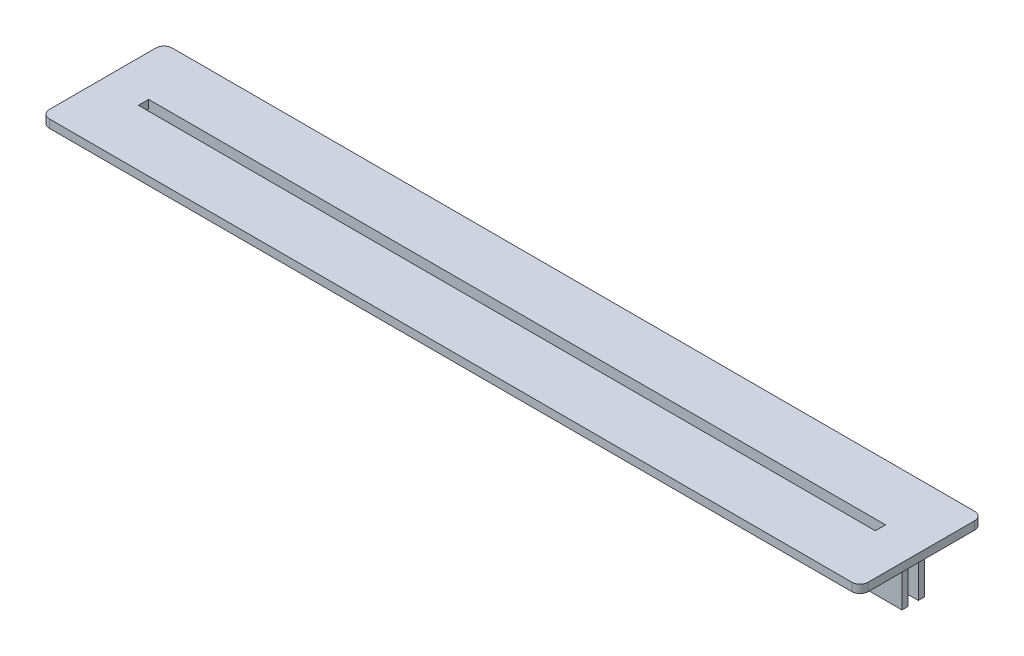
SolidWorks part; units mm, degrees
ref_plane "Front Plane" through (0, 0, 0) normal (0, 0, 1) x (1, 0, 0)
ref_plane "Top Plane" through (0, 0, 0) normal (0, 1, 0) x (1, 0, 0)
ref_plane "Right Plane" through (0, 0, 0) normal (1, 0, 0) x (0, 0, -1)
sketch "Sketch3" plane through (0, 0, 0) normal (0, 1, 0) x (1, 0, 0)
  line L1 (-124.46, 19.05) -> (124.46, 19.05)
  line L2 (-127, 16.51) -> (-127, -16.51)
  line L3 (-124.46, -19.05) -> (124.46, -19.05)
  line L4 (127, 16.51) -> (127, -16.51)
  line L5 (-127, 19.05) -> (127, -19.05) construction
  line L6 (-127, -19.05) -> (127, 19.05) construction
  arc A0 (124.46, -19.05) -> (127, -16.51) centre (124.46, -16.51) ccw
  arc A1 (124.46, 19.05) -> (127, 16.51) centre (124.46, 16.51) cw
  arc A2 (-127, -16.51) -> (-124.46, -19.05) centre (-124.46, -16.51) ccw
  arc A3 (-124.46, 19.05) -> (-127, 16.51) centre (-124.46, 16.51) ccw
  point P0 (0, 0)
  dimension "D3" = 2.54
  dimension "D1" = 254
  dimension "D2" = 38.1
extrude "Boss-Extrude1" add sketch "Sketch3" along normal blind 2.54
sketch "Sketch4" plane through (0, 0, 0) normal (1, 0, 0) x (0, 0, -1)
  line L0 (-16.51, 0) -> (-16.51, -12.7)
  line L1 (-16.51, -12.7) -> (-14.5796, -12.7)
  line L2 (-14.5796, -12.7) -> (-14.5796, 0)
  line L3 (-16.51, 0) -> (16.51, 0) construction
  line L4 (-14.5796, 0) -> (-16.51, 0)
  line L5 (0, 10.2591) -> (0, -16.4007) construction
  line L6 (14.5796, 0) -> (16.51, 0)
  line L7 (14.5796, -12.7) -> (14.5796, 0)
  line L8 (16.51, -12.7) -> (14.5796, -12.7)
  line L9 (16.51, 0) -> (16.51, -12.7)
  dimension "D1" = 1.9304
  dimension "D2" = 12.7
sketch "Sketch5" plane through (0, 0, 0) normal (0, 1, 0) x (1, 0, 0)
  line L1 (-114.3, 1.5875) -> (114.3, 1.5875)
  line L2 (-114.3, 1.5875) -> (-114.3, -1.5875)
  line L3 (-114.3, -1.5875) -> (114.3, -1.5875)
  line L4 (114.3, 1.5875) -> (114.3, -1.5875)
  line L5 (-114.3, 1.5875) -> (114.3, -1.5875) construction
  line L6 (-114.3, -1.5875) -> (114.3, 1.5875) construction
  point P0 (0, 0)
  dimension "D1" = 3.175
  dimension "D2" = 228.6
extrude "Cut-Extrude1" cut sketch "Sketch5" against normal up to surface (2.54 mm away) from surface at 2.54 up to face at (0, 0, 0) starting at face at (0, 2.54, 0)
sketch "Sketch6" plane through (0, 0, 0) normal (0, -1, 0) x (1, 0, 0)
  line L0 (-160.0471, 0) -> (175.8267, 0) construction
  line L1 (-124.46, -3.4925) -> (124.46, -3.4925)
  line L2 (-124.46, 1.5875) -> (124.46, 1.5875)
  line L4 (-124.46, 3.4925) -> (124.46, 3.4925)
  line L7 (-124.46, -1.5875) -> (124.46, -1.5875)
  line L8 (-124.46, -1.5875) -> (-124.46, -3.4925)
  line L9 (-114.3, 1.5875) -> (114.3, 1.5875) construction
  line L10 (-124.46, 3.4925) -> (-124.46, 1.5875)
  line L11 (-127, -16.51) -> (-127, 16.51) construction
  line L12 (124.46, 3.4925) -> (124.46, 1.5875)
  line L13 (124.46, -1.5875) -> (124.46, -3.4925)
  line L14 (127, 16.51) -> (127, -16.51) construction
  dimension "D1" = 1.905
  dimension "D2" = 2.54
  dimension "D3" = 2.54
extrude "Boss-Extrude3" add sketch "Sketch6" along normal blind 12.7 from surface at 0 starting at face at (0, 0, 0)
